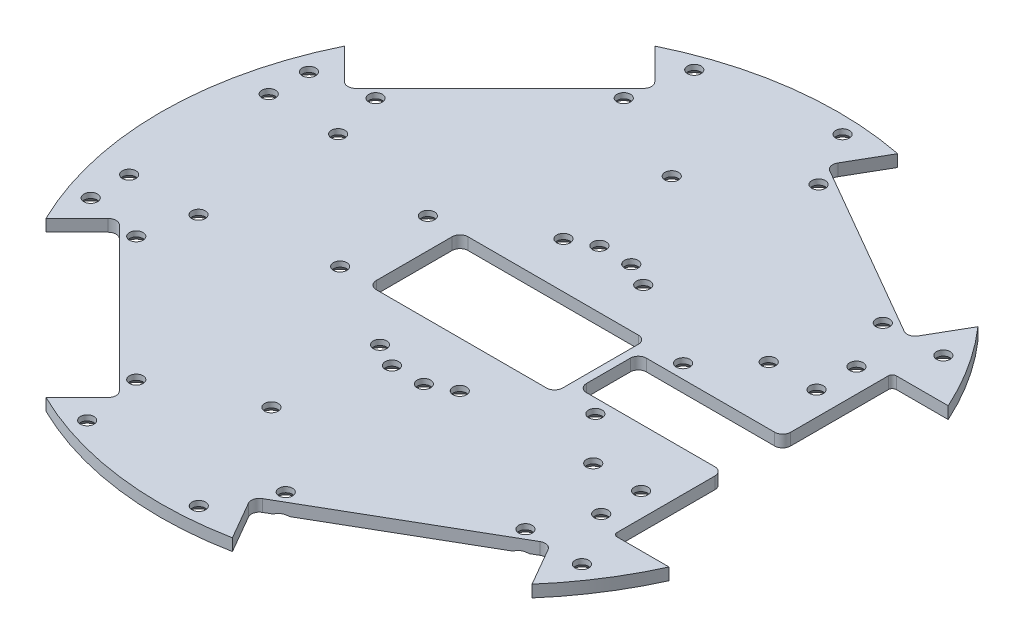
SolidWorks part; units mm, degrees
material "Liga 6061"
ref_plane "Plano frontal" through (0, 0, 0) normal (0, 0, 1) x (1, 0, 0)
ref_plane "Plano superior" through (0, 0, 0) normal (0, 1, 0) x (1, 0, 0)
ref_plane "Plano direito" through (0, 0, 0) normal (1, 0, 0) x (0, 0, -1)
sketch "Esboço1" plane through (0, 0, 0) normal (0, 1, 0) x (1, 0, 0)
  line L0 (0, -20.0389) -> (0, 0) construction
  line L1 (0, 0) -> (-50000, 0) construction
  line L2 (0, 0) -> (-35355.3391, -35355.3391) construction
  line L3 (-76.317, -37.4261) -> (-37.4261, -76.317) construction
  line L4 (16.3986, -83.4032) -> (64.03, -55.9032) construction
  line L5 (0, 0) -> (25000, -43301.2702) construction
  line L6 (16.3986, 83.4032) -> (64.03, 55.9032) construction
  line L7 (-76.317, 37.4261) -> (-37.4261, 76.317) construction
  line L8 (-61.1142, -30.0015) -> (-30.0015, -61.1142) construction
  line L9 (13.1617, -66.7968) -> (51.2668, -44.7968) construction
  line L10 (-67.1246, -28.2337) -> (-28.2337, -67.1246)
  line L15 (-67.1246, -28.2337) -> (-76.317, -37.4261)
  line L16 (-28.2337, -67.1246) -> (-37.4261, -76.317)
  line L17 (9.8986, -72.1448) -> (57.53, -44.6448)
  line L18 (64.03, -55.9032) -> (57.53, -44.6448)
  line L19 (16.3986, -83.4032) -> (9.8986, -72.1448)
  line L20 (64.03, 55.9032) -> (57.53, 44.6448)
  line L21 (9.8986, 72.1448) -> (57.53, 44.6448)
  line L22 (16.3986, 83.4032) -> (9.8986, 72.1448)
  line L23 (-28.2337, 67.1246) -> (-37.4261, 76.317)
  line L24 (-67.1246, 28.2337) -> (-28.2337, 67.1246)
  line L25 (-67.1246, 28.2337) -> (-76.317, 37.4261)
  line L28 (0, 0) -> (-75.1754, 27.3616) construction
  line L29 (-9.6973, 69) -> (0, 0) construction
  line L31 (0, 0) -> (65.9301, 45.3125) construction
  line L32 (3, 127.8652) -> (3, -125.0226) construction
  line L34 (0, 85) -> (0, 66.7968) construction
  arc A0 (-37.4261, -76.317) -> (16.3986, -83.4032) centre (0, 0) ccw
  arc A1 (64.03, -55.9032) -> (64.03, 55.9032) centre (0, 0) ccw
  arc A2 (-76.317, 37.4261) -> (-76.317, -37.4261) centre (0, 0) ccw
  arc A3 (16.3986, 83.4032) -> (-37.4261, 76.317) centre (0, 0) ccw
  circle A4 centre (-61.1142, -30.0015) radius 1.7
  circle A5 centre (-30.0015, -61.1142) radius 1.7
  circle A6 centre (13.1617, -66.7968) radius 1.7
  circle A7 centre (51.2668, -44.7968) radius 1.7
  circle A8 centre (-61.1142, 30.0015) radius 1.7
  circle A9 centre (-30.0015, 61.1142) radius 1.7
  circle A10 centre (13.1617, 66.7968) radius 1.7
  circle A11 centre (51.2668, 44.7968) radius 1.7
  circle A14 centre (-75.3985, 17.5) radius 1.5
  circle A15 centre (-58, 17.5) radius 1.5
  circle A16 centre (-58, -17.5) radius 1.5
  circle A17 centre (-75.3985, -17.5) radius 1.5
  circle A24 centre (-27.3176, 76.108) radius 1.5
  circle A32 centre (-75.1754, 27.3616) radius 1.5
  circle A33 centre (65.9301, 45.3125) radius 1.5
  circle A34 centre (65.9301, -45.3125) radius 1.5
  circle A35 centre (-75.1754, -27.3616) radius 1.5
  circle A36 centre (7, -26) radius 1.5
  circle A37 centre (13, -23) radius 1.5
  circle A38 centre (35, -11) radius 1.5
  circle A48 centre (5.2686, 80.7056) radius 1.5
  circle A49 centre (-7.0429, 50.1863) radius 1.5
  circle A50 centre (-27.3176, -76.108) radius 1.5
  circle A51 centre (5.2686, -80.7056) radius 1.5
  circle A52 centre (-7.0429, -50.1863) radius 1.5
  circle A53 centre (-29, -11) radius 1.5
  circle A54 centre (-7, -23) radius 1.5
  circle A55 centre (-1, -26) radius 1.5
  circle A56 centre (35, 11) radius 1.5
  circle A57 centre (13, 23) radius 1.5
  circle A58 centre (7, 26) radius 1.5
  circle A59 centre (-1, 26) radius 1.5
  circle A60 centre (-7, 23) radius 1.5
  circle A61 centre (-29, 11) radius 1.5
  point P6 (0, 0)
  point P13 (-56.8716, -56.8716)
  point P14 (51.2668, 44.7968)
  point P17 (40.2143, -69.6532)
  point P21 (-45.5579, -45.5579)
  point P24 (32.2143, -55.7968)
  point P25 (13.1617, 66.7968)
  point P26 (-30.0015, 61.1142)
  point P27 (-61.1142, 30.0015)
  point P42 (-27.3176, 76.108)
  point P48 (-47.6792, -47.6792)
  point P51 (33.7143, -58.3948)
  point P52 (-71.7208, -32.8299)
  point P57 (-71.7208, 32.8299)
  point P63 (-75.3985, 17.5)
  point P64 (-58, 17.5)
  point P73 (-9.6883, 68.9348)
  point P80 (-9.6973, 69)
  point P113 (-9.6973, 69)
  dimension "D1" = 170
  dimension "D6" = 3.4
  dimension "D12" = 7
  dimension "D17" = 3
  dimension "D18" = 3
  dimension "D11" = 3
  dimension "D14" = 58
  dimension "D10" = 3
  dimension "D22" = 3
  dimension "D23" = 3
  dimension "D24" = 3
  dimension "D25" = 3
  dimension "D26" = 3
  dimension "D29" = 26
  dimension "D30" = 4
  dimension "D31" = 10
  dimension "D32" = 32
  dimension "D2" = 45
  dimension "D3" = 55
  dimension "D4" = 30
  dimension "D5" = 44
  dimension "D7" = 69
  dimension "D8" = 82
  dimension "D9" = 19
  dimension "D13" = 17.3985
  dimension "D15" = 20
  dimension "D16" = 17.5
  dimension "D19" = 34.5
  dimension "D20" = 80
  dimension "D21" = 80
  dimension "D27" = 11
  dimension "D28" = 23
  dimension "D33" = 3
extrude "Base" add sketch "Esboço1" along normal blind 3
sketch "Esboço21" plane through (0, 0, 0) normal (0, -1, 0) x (1, 0, 0)
  line L0 (0, 0) -> (50000, 0) construction
  line L2 (63.4597, -35) -> (77.4597, -35)
  line L3 (63.4597, -35) -> (63.4597, 35)
  line L4 (63.4597, 35) -> (77.4597, 35)
  line L6 (63.4597, -35) -> (77.4597, 35) construction
  line L7 (63.4597, 35) -> (77.4597, -35) construction
  arc A0 (77.4597, 35) -> (77.4597, -35) centre (0, 0) cw
  circle A1 centre (57.4597, 32) radius 1.5
  circle A2 centre (57.4597, 22) radius 1.5
  circle A3 centre (45.4597, 22) radius 1.5
  circle A4 centre (45.4597, -22) radius 1.5
  circle A5 centre (57.4597, -22) radius 1.5
  circle A6 centre (57.4597, -32) radius 1.5
  point P3 (70.4597, 0)
  point P9 (57.4597, 32)
  point P10 (57.4597, 22)
  point P11 (45.4597, 22)
  dimension "D8" = 3
  dimension "D9" = 3
  dimension "D10" = 3
  dimension "D1" = 70
  dimension "D2" = 14
  dimension "D3" = 85
  dimension "D4" = 3
  dimension "D5" = 10
  dimension "D6" = 12
  dimension "D7" = 6
extrude "Boca Chute" cut sketch "Esboço21" against normal blind 20
sketch "Esboço32" plane through (63.4597, 0, 0) normal (1, 0, 0) x (0, 0, -1)
  line L0 (0, 7.9765) -> (0, -7.5498) construction
  line L1 (-35, 1.5) -> (35, 1.5) construction
  line L2 (-35, 3) -> (-35, 0) construction
  line L3 (35, 3) -> (35, 0) construction
  line L4 (35, 3) -> (-35, 3) construction
  line L5 (-7.5, 0) -> (7.5, 0)
  line L6 (-7.5, 0) -> (-7.5, 3)
  line L7 (-7.5, 3) -> (7.5, 3)
  line L8 (7.5, 0) -> (7.5, 3)
  line L9 (-7.5, 0) -> (7.5, 3) construction
  line L10 (-7.5, 3) -> (7.5, 0) construction
  point P9 (0, 1.5)
  dimension "D1" = 15
extrude "Corte-extrusão2" cut sketch "Esboço32" against normal blind 36.19
sketch "Esboço33" plane through (0, 3, 0) normal (0, 1, 0) x (1, 0, 0)
  line L0 (57.9822, 0) -> (-158.875, 0) construction
  line L1 (27.2697, 7.5) -> (27.2697, -7.5) construction
  line L2 (-21.4303, -11.5) -> (25.2697, -11.5)
  line L3 (-21.4303, -11.5) -> (-21.4303, 11.5)
  line L4 (-21.4303, 11.5) -> (25.2697, 11.5)
  line L5 (25.2697, -11.5) -> (25.2697, 11.5)
  line L6 (-21.4303, -11.5) -> (25.2697, 11.5) construction
  line L7 (-21.4303, 11.5) -> (25.2697, -11.5) construction
  point P1 (1.9197, 0)
  dimension "D1" = 2
  dimension "D2" = 46.7
  dimension "D3" = 23
extrude "Corte-extrusão3" cut sketch "Esboço33" against normal through all
hole_wizard "Escareado para SFHCS M31" positions "Esboço34" profile "Esboço35" countersink size "M3" standard "Ansi Metric" end condition through all
sketch "Esboço34" plane through (0, 0, 0) normal (0, -1, 0) x (-1, 0, 0)
  point P0 (-65.9301, 45.3125)
  point P3 (-57.4597, 32)
  point P6 (-57.4597, 22)
  point P9 (-51.2668, 44.7968)
  point P12 (-45.4597, 22)
  point P15 (-35, 11)
  point P18 (-13.1617, 66.7968)
  point P21 (-5.2686, 80.7056)
  point P24 (7.0429, 50.1863)
  point P27 (1, 26)
  point P30 (-7, 26)
  point P33 (-13, 23)
  point P36 (7, 23)
  point P39 (7.0429, 50.1863)
  point P41 (27.3176, 76.108)
  point P44 (30.0015, 61.1142)
  point P47 (29, 11)
  point P50 (61.1142, 30.0015)
  point P53 (58, 17.5)
  point P56 (75.3985, 17.5)
  point P59 (75.1754, 27.3616)
  point P62 (-35, -11)
  point P65 (-45.4597, -22)
  point P68 (-57.4597, -22)
  point P71 (-57.4597, -32)
  point P74 (-65.9301, -45.3125)
  point P77 (-51.2668, -44.7968)
  point P80 (-13.1617, -66.7968)
  point P83 (-5.2686, -80.7056)
  point P86 (7.0429, -50.1863)
  point P89 (-13, -23)
  point P92 (-7, -26)
  point P95 (1, -26)
  point P98 (7, -23)
  point P101 (30.0015, -61.1142)
  point P104 (27.3176, -76.108)
  point P107 (29, -11)
  point P110 (58, -17.5)
  point P113 (75.3985, -17.5)
  point P116 (75.1754, -27.3616)
  point P119 (61.1142, -30.0015)
sketch "Esboço35" plane through (65.9301, 0, -45.3125) normal (1, 0, 0) x (0, 0, -1)
  line L0 (0, 0) -> (0, 3)
  line L1 (0, 3) -> (1.7, 3)
  line L2 (1.7, 3) -> (1.7, 1.66)
  line L3 (1.7, 1.66) -> (3.36, 0)
  line L5 (3.36, 0) -> (0, 0)
  line L6 (-1.7, 1.66) -> (-3.36, 0) construction
  line L11 (0, -6.35) -> (0, 107.95) construction
  dimension "Thru Hole Dia." = 3.4
  dimension "Thru Hole Depth" = 3
  dimension "Near C'Sink Dia." = 6.72
  dimension "Near C'Sink Angle" = 90
fillet "Filete1" radius 2 16 edges at (25.2697, 1.5, 11.5) (25.2697, 1.5, -11.5) (-21.4303, 1.5, -11.5) (-21.4303, 1.5, 11.5) (63.4597, 1.5, 7.5) (63.4597, 1.5, -7.5) (27.2697, 1.5, 7.5) (27.2697, 1.5, -7.5) (9.8986, 1.5, -72.1448) (57.53, 1.5, -44.6448) (-67.1246, 1.5, -28.2337) (-28.2337, 1.5, -67.1246) (-67.1246, 1.5, 28.2337) (-28.2337, 1.5, 67.1246) (9.8986, 1.5, 72.1448) (57.53, 1.5, 44.6448)
fillet "Filete2" radius 1 2 edges at (63.4597, 1.5, -35) (63.4597, 1.5, 35)
